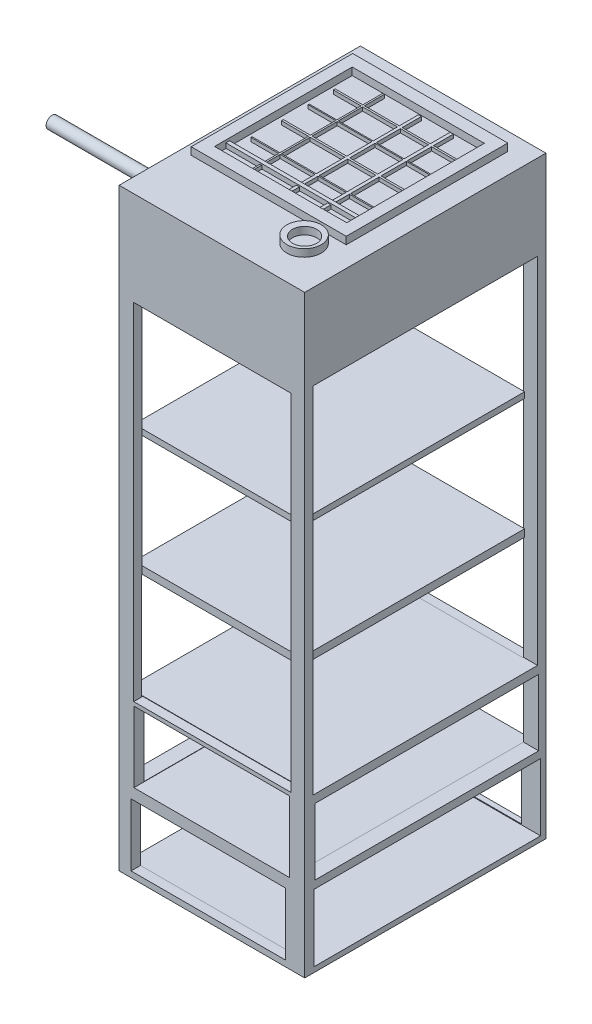
SolidWorks part; units mm, degrees
ref_plane "Front Plane" through (0, 0, 0) normal (0, 0, 1) x (1, 0, 0)
ref_plane "Top Plane" through (0, 0, 0) normal (0, 1, 0) x (1, 0, 0)
ref_plane "Right Plane" through (0, 0, 0) normal (1, 0, 0) x (0, 0, -1)
sketch "Sketch1" plane through (0, 0, 0) normal (1, 0, 0) x (0, 0, -1)
  line L1 (-32.5, 70.6888) -> (32.5, 70.6888)
  line L2 (-32.5, 70.6888) -> (-32.5, -89.3112)
  line L3 (-32.5, -89.3112) -> (32.5, -89.3112)
  line L4 (32.5, 70.6888) -> (32.5, -89.3112)
  line L5 (-30.264, 47.7422) -> (30.264, 47.7422)
  line L6 (-30.264, 47.7422) -> (-30.264, -47.7422)
  line L7 (-30.264, -47.7422) -> (30.264, -47.7422)
  line L8 (30.264, 47.7422) -> (30.264, -47.7422)
  point P0 (0, 0)
  point P7 (0, 0)
  dimension "D1" = 65
  dimension "D2" = 160
extrude "Boss-Extrude1" add sketch "Sketch1" along normal blind 50
sketch "Sketch2" plane through (0, 0, -32.5) normal (0, 0, -1) x (-1, 0, 0)
  line L1 (-46.2524, 45.3137) -> (-3.9263, 45.3137)
  line L2 (-46.2524, 45.3137) -> (-46.2524, -47.8418)
  line L3 (-46.2524, -47.8418) -> (-3.9263, -47.8418)
  line L4 (-3.9263, 45.3137) -> (-3.9263, -47.8418)
  line L5 (-46.2524, 45.3137) -> (-3.9263, -47.8418) construction
  line L6 (-46.2524, -47.8418) -> (-3.9263, 45.3137) construction
  point P0 (-25.0894, -1.2641)
extrude "Cut-Extrude1" cut sketch "Sketch2" against normal through all
sketch "Sketch3" plane through (0, -47.8418, 0) normal (0, 1, 0) x (1, 0, 0)
  line L1 (1.5977, 30.0906) -> (46.6551, 30.0906)
  line L2 (1.5977, 30.0906) -> (1.5977, -30.0603)
  line L3 (1.5977, -30.0603) -> (46.6551, -30.0603)
  line L4 (46.6551, 30.0906) -> (46.6551, -30.0603)
  line L5 (1.5977, 30.0906) -> (46.6551, -30.0603) construction
  line L6 (1.5977, -30.0603) -> (46.6551, 30.0906) construction
  point P0 (24.1264, 0.0152)
extrude "Boss-Extrude2" add sketch "Sketch3" along normal through all
sketch "Sketch4" plane through (1.5977, 0, 0) normal (-1, 0, 0) x (0, 0, 1)
  line L0 (30.264, 47.7422) -> (30.264, -47.7422) construction
  line L1 (-30.1177, 47.4229) -> (30.264, 47.4229)
  line L2 (-30.1177, 47.4229) -> (-30.1177, 14.5309)
  line L3 (-30.1177, 14.5309) -> (30.264, 14.5309)
  line L4 (30.264, 47.4229) -> (30.264, 14.5309)
  line L5 (-30.1177, 47.4229) -> (30.264, 14.5309) construction
  line L6 (-30.1177, 14.5309) -> (30.264, 47.4229) construction
  point P0 (0.0732, 30.9769)
extrude "Cut-Extrude2" cut sketch "Sketch4" against normal through all
sketch "Sketch5" plane through (46.6551, 0, 0) normal (1, 0, 0) x (0, 0, -1)
  line L1 (-30.1757, 12.9564) -> (30.2072, 12.9564)
  line L2 (-30.1757, 12.9564) -> (-30.1757, -17.4422)
  line L3 (-30.1757, -17.4422) -> (30.2072, -17.4422)
  line L4 (30.2072, 12.9564) -> (30.2072, -17.4422)
  line L5 (-30.1757, 12.9564) -> (30.2072, -17.4422) construction
  line L6 (-30.1757, -17.4422) -> (30.2072, 12.9564) construction
  point P0 (0.0157, -2.2429)
extrude "Cut-Extrude3" cut sketch "Sketch5" against normal through all
sketch "Sketch6" plane through (46.6551, 0, 0) normal (1, 0, 0) x (0, 0, -1)
  line L0 (30.0906, -17.4422) -> (30.0906, -47.7422) construction
  line L1 (-30.3597, -19.4422) -> (30.0906, -19.4422)
  line L2 (-30.3597, -19.4422) -> (-30.3597, -47.7422)
  line L3 (-30.3597, -47.7422) -> (30.0906, -47.7422)
  line L4 (30.0906, -19.4422) -> (30.0906, -47.7422)
  line L5 (-30.3597, -19.4422) -> (30.0906, -47.7422) construction
  line L6 (-30.3597, -47.7422) -> (30.0906, -19.4422) construction
  point P0 (-0.1345, -33.5922)
extrude "Cut-Extrude4" cut sketch "Sketch6" against normal through all
sketch "Sketch7" plane through (50, 0, 0) normal (1, 0, 0) x (0, 0, -1)
  line L1 (-29.7434, -49.9682) -> (30.5607, -49.9682)
  line L2 (-29.7434, -49.9682) -> (-29.7434, -67.8351)
  line L3 (-29.7434, -67.8351) -> (30.5607, -67.8351)
  line L4 (30.5607, -49.9682) -> (30.5607, -67.8351)
  line L5 (-29.7434, -49.9682) -> (30.5607, -67.8351) construction
  line L6 (-29.7434, -67.8351) -> (30.5607, -49.9682) construction
  point P0 (0.4086, -58.9016)
extrude "Cut-Extrude5" cut sketch "Sketch7" against normal through all
sketch "Sketch8" plane through (0, 0, 32.5) normal (0, 0, 1) x (1, 0, 0)
  line L1 (3.9687, -48.8665) -> (45.9067, -48.8665)
  line L2 (3.9687, -48.8665) -> (3.9687, -67.9169)
  line L3 (3.9687, -67.9169) -> (45.9067, -67.9169)
  line L4 (45.9067, -48.8665) -> (45.9067, -67.9169)
  line L5 (3.9687, -48.8665) -> (45.9067, -67.9169) construction
  line L6 (3.9687, -67.9169) -> (45.9067, -48.8665) construction
  point P0 (24.9377, -58.3917)
extrude "Cut-Extrude6" cut sketch "Sketch8" against normal through all
sketch "Sketch10" plane through (50, 0, 0) normal (1, 0, 0) x (0, 0, -1)
  line L1 (-29.9701, -69.8781) -> (31.0694, -69.8781)
  line L2 (-29.9701, -69.8781) -> (-29.9701, -87.932)
  line L3 (-29.9701, -87.932) -> (31.0694, -87.932)
  line L4 (31.0694, -69.8781) -> (31.0694, -87.932)
  line L5 (-29.9701, -69.8781) -> (31.0694, -87.932) construction
  line L6 (-29.9701, -87.932) -> (31.0694, -69.8781) construction
  point P0 (0.5496, -78.9051)
extrude "Cut-Extrude10" cut sketch "Sketch10" against normal through all
sketch "Sketch11" plane through (0, 0, -32.5) normal (0, 0, -1) x (-1, 0, 0)
  line L1 (-44.859, -70.8929) -> (-3.2128, -70.8929)
  line L2 (-44.859, -70.8929) -> (-44.859, -87.7146)
  line L3 (-44.859, -87.7146) -> (-3.2128, -87.7146)
  line L4 (-3.2128, -70.8929) -> (-3.2128, -87.7146)
  line L5 (-44.859, -70.8929) -> (-3.2128, -87.7146) construction
  line L6 (-44.859, -87.7146) -> (-3.2128, -70.8929) construction
  point P0 (-24.0359, -79.3038)
extrude "Cut-Extrude11" cut sketch "Sketch11" against normal through all
sketch "Sketch12" plane through (0, 0, 0) normal (-1, 0, 0) x (0, 0, 1)
  line L1 (-30.2872, 67.0104) -> (19.3028, 67.0104)
  line L2 (-30.2872, 67.0104) -> (-30.2872, 50.3789)
  line L3 (-30.2872, 50.3789) -> (19.3028, 50.3789)
  line L4 (19.3028, 67.0104) -> (19.3028, 50.3789)
  line L5 (-29.1753, 65.6203) -> (18.1249, 65.6203)
  line L6 (-29.1753, 65.6203) -> (-29.1753, 51.7691)
  line L7 (-29.1753, 51.7691) -> (18.1249, 51.7691)
  line L8 (18.1249, 65.6203) -> (18.1249, 51.7691)
  point P0 (2.9716, 58.6947)
  point P6 (2.6855, 58.6947)
extrude "Boss-Extrude3" add sketch "Sketch12" along normal blind 1
sketch "Sketch13" plane through (0, 0, 0) normal (-1, 0, 0) x (0, 0, 1)
  line L1 (-28.2976, 64.7358) -> (17.5421, 64.7358)
  line L2 (-28.2976, 64.7358) -> (-28.2976, 63.8455)
  line L3 (-28.2976, 63.8455) -> (17.5421, 63.8455)
  line L4 (17.5421, 64.7358) -> (17.5421, 63.8455)
  line L5 (-28.2976, 64.7358) -> (17.5421, 63.8455) construction
  line L6 (-28.2976, 63.8455) -> (17.5421, 64.7358) construction
  line L7 (-28.1792, 62.5078) -> (17.7258, 62.5078)
  line L8 (-28.1792, 62.5078) -> (-28.1792, 61.2255)
  line L9 (-28.1792, 61.2255) -> (17.7258, 61.2255)
  line L10 (17.7258, 62.5078) -> (17.7258, 61.2255)
  line L11 (-28.1792, 62.5078) -> (17.7258, 61.2255) construction
  line L12 (-28.1792, 61.2255) -> (17.7258, 62.5078) construction
  line L13 (-28.1711, 60.0546) -> (17.674, 60.0546)
  line L14 (-28.1711, 60.0546) -> (-28.1711, 59.0796)
  line L15 (-28.1711, 59.0796) -> (17.674, 59.0796)
  line L16 (17.674, 60.0546) -> (17.674, 59.0796)
  line L17 (-28.1711, 60.0546) -> (17.674, 59.0796) construction
  line L18 (-28.1711, 59.0796) -> (17.674, 60.0546) construction
  line L19 (-28.0186, 58.0084) -> (17.713, 58.0084)
  line L20 (-28.0186, 58.0084) -> (-28.0186, 57.1447)
  line L21 (-28.0186, 57.1447) -> (17.713, 57.1447)
  line L22 (17.713, 58.0084) -> (17.713, 57.1447)
  line L23 (-28.0186, 58.0084) -> (17.713, 57.1447) construction
  line L24 (-28.0186, 57.1447) -> (17.713, 58.0084) construction
  line L25 (-28.049, 56.7273) -> (17.6489, 56.7273)
  line L26 (-28.049, 56.7273) -> (-28.049, 55.6053)
  line L27 (-28.049, 55.6053) -> (17.6489, 55.6053)
  line L28 (17.6489, 56.7273) -> (17.6489, 55.6053)
  line L29 (-28.049, 56.7273) -> (17.6489, 55.6053) construction
  line L30 (-28.049, 55.6053) -> (17.6489, 56.7273) construction
  line L31 (-27.9542, 55.005) -> (17.5549, 55.005)
  line L32 (-27.9542, 55.005) -> (-27.9542, 54.2102)
  line L33 (-27.9542, 54.2102) -> (17.5549, 54.2102)
  line L34 (17.5549, 55.005) -> (17.5549, 54.2102)
  line L35 (-27.9542, 55.005) -> (17.5549, 54.2102) construction
  line L36 (-27.9542, 54.2102) -> (17.5549, 55.005) construction
  line L37 (-28.0211, 53.4431) -> (17.3054, 53.4431)
  line L38 (-28.0211, 53.4431) -> (-28.0211, 52.6483)
  line L39 (-28.0211, 52.6483) -> (17.3054, 52.6483)
  line L40 (17.3054, 53.4431) -> (17.3054, 52.6483)
  line L41 (-28.0211, 53.4431) -> (17.3054, 52.6483) construction
  line L42 (-28.0211, 52.6483) -> (17.3054, 53.4431) construction
  point P0 (-5.3777, 64.2907)
  point P5 (-5.2486, 59.5671)
  point P6 (-5.2267, 61.8666)
  point P15 (-5.1528, 57.5766)
  point P20 (-5.2, 56.1663)
  point P25 (-5.1996, 54.6076)
  point P30 (-5.3579, 53.0457)
extrude "Boss-Extrude4" add sketch "Sketch13" along normal blind 1
sketch "Sketch17" plane through (0, 0, 0) normal (-1, 0, 0) x (0, 0, 1)
  circle A0 centre (22.5775, 66.4593) radius 1.6078
extrude "Boss-Extrude7" add sketch "Sketch17" along normal blind 28
sketch "Sketch18" plane through (0, -67.9169, 0) normal (0, 1, 0) x (1, 0, 0)
  line L1 (19.2354, 28.2996) -> (8.2979, 28.2996)
  line L2 (19.2354, 28.2996) -> (19.2354, 11.6786)
  line L3 (19.2354, 11.6786) -> (8.2979, 11.6786)
  line L4 (8.2979, 28.2996) -> (8.2979, 11.6786)
  line L5 (19.2354, 28.2996) -> (8.2979, 11.6786) construction
  line L6 (19.2354, 11.6786) -> (8.2979, 28.2996) construction
  point P0 (13.7666, 19.9891)
extrude "Boss-Extrude9" add sketch "Sketch18" along normal blind 10
sketch "Sketch19" plane through (0, 70.6888, 0) normal (0, 1, 0) x (1, 0, 0)
  circle A0 centre (38.4512, -21.1125) radius 4.6271
  circle A1 centre (38.8925, -21.4164) radius 3.27
extrude "Boss-Extrude10" add sketch "Sketch19" along normal blind 2
sketch "Sketch20" plane through (0, 70.6888, 0) normal (0, 1, 0) x (1, 0, 0)
  line L1 (44.496, 27.7166) -> (2.7156, 27.7166)
  line L2 (44.496, 27.7166) -> (44.496, -15.8024)
  line L3 (44.496, -15.8024) -> (2.7156, -15.8024)
  line L4 (2.7156, 27.7166) -> (2.7156, -15.8024)
  line L5 (44.496, 27.7166) -> (2.7156, -15.8024) construction
  line L6 (44.496, -15.8024) -> (2.7156, 27.7166) construction
  line L7 (41.4078, 24.4999) -> (5.8038, 24.4999)
  line L8 (41.4078, 24.4999) -> (41.4078, -12.5857)
  line L9 (41.4078, -12.5857) -> (5.8038, -12.5857)
  line L10 (5.8038, 24.4999) -> (5.8038, -12.5857)
  line L11 (41.4078, 24.4999) -> (5.8038, -12.5857) construction
  line L12 (41.4078, -12.5857) -> (5.8038, 24.4999) construction
  point P0 (23.6058, 5.9571)
  point P7 (23.6058, 5.9571)
extrude "Boss-Extrude11" add sketch "Sketch20" along normal blind 2
sketch "Sketch21" plane through (0, 70.6888, 0) normal (0, 1, 0) x (1, 0, 0)
  line L1 (40.4992, 17.61) -> (7.6115, 17.61)
  line L2 (40.4992, 17.61) -> (40.4992, 18.0971)
  line L3 (40.4992, 18.0971) -> (7.6115, 18.0971)
  line L4 (7.6115, 17.61) -> (7.6115, 18.0971)
  line L5 (40.4992, 17.61) -> (7.6115, 18.0971) construction
  line L6 (40.4992, 18.0971) -> (7.6115, 17.61) construction
  line L7 (40.4707, 10.775) -> (7.6571, 10.775)
  line L8 (40.4707, 10.775) -> (40.4707, 11.0739)
  line L9 (40.4707, 11.0739) -> (7.6571, 11.0739)
  line L10 (7.6571, 10.775) -> (7.6571, 11.0739)
  line L11 (40.4707, 10.775) -> (7.6571, 11.0739) construction
  line L12 (40.4707, 11.0739) -> (7.6571, 10.775) construction
  line L13 (40.906, 3.9577) -> (7.8021, 3.9577)
  line L14 (40.906, 3.9577) -> (40.906, 3.4384)
  line L15 (40.906, 3.4384) -> (7.8021, 3.4384)
  line L16 (7.8021, 3.9577) -> (7.8021, 3.4384)
  line L17 (40.906, 3.9577) -> (7.8021, 3.4384) construction
  line L18 (40.906, 3.4384) -> (7.8021, 3.9577) construction
  line L19 (40.4476, -4.5868) -> (7.5662, -4.5868)
  line L20 (40.4476, -4.5868) -> (40.4476, -4.2522)
  line L21 (40.4476, -4.2522) -> (7.5662, -4.2522)
  line L22 (7.5662, -4.5868) -> (7.5662, -4.2522)
  line L23 (40.4476, -4.5868) -> (7.5662, -4.2522) construction
  line L24 (40.4476, -4.2522) -> (7.5662, -4.5868) construction
  point P0 (24.0553, 17.8536)
  point P5 (24.354, 3.6981)
  point P6 (24.0639, 10.9244)
  point P15 (24.0069, -4.4195)
extrude "Boss-Extrude12" add sketch "Sketch21" along normal blind 1
sketch "Sketch22" plane through (0, 70.6888, 0) normal (0, 1, 0) x (1, 0, 0)
  line L1 (34.0968, 23.4506) -> (33.2223, 23.4506)
  line L2 (34.0968, 23.4506) -> (34.0968, -12.1702)
  line L3 (34.0968, -12.1702) -> (33.2223, -12.1702)
  line L4 (33.2223, 23.4506) -> (33.2223, -12.1702)
  line L5 (34.0968, 23.4506) -> (33.2223, -12.1702) construction
  line L6 (34.0968, -12.1702) -> (33.2223, 23.4506) construction
  line L7 (24.8719, 23.2806) -> (25.6704, 23.2806)
  line L8 (24.8719, 23.2806) -> (24.8719, -12.1702)
  line L9 (24.8719, -12.1702) -> (25.6704, -12.1702)
  line L10 (25.6704, 23.2806) -> (25.6704, -12.1702)
  line L11 (24.8719, 23.2806) -> (25.6704, -12.1702) construction
  line L12 (24.8719, -12.1702) -> (25.6704, 23.2806) construction
  line L13 (15.0677, 23.5067) -> (15.4979, 23.5067)
  line L14 (15.0677, 23.5067) -> (15.0677, -12.1702)
  line L15 (15.0677, -12.1702) -> (15.4979, -12.1702)
  line L16 (15.4979, 23.5067) -> (15.4979, -12.1702)
  line L17 (15.0677, 23.5067) -> (15.4979, -12.1702) construction
  line L18 (15.0677, -12.1702) -> (15.4979, 23.5067) construction
  point P0 (33.6596, 5.6402)
  point P5 (25.2711, 5.5552)
  point P11 (15.2828, 5.6682)
extrude "Boss-Extrude13" add sketch "Sketch22" along normal blind 1
sketch "Sketch23" plane through (41.4078, 0, 0) normal (-1, 0, 0) x (0, 0, 1)
  line L1 (8.5733, 72.0321) -> (9.5687, 72.0321)
  line L2 (8.5733, 72.0321) -> (8.5733, 70.7591)
  line L3 (8.5733, 70.7591) -> (9.5687, 70.7591)
  line L4 (9.5687, 72.0321) -> (9.5687, 70.7591)
  line L5 (8.5733, 72.0321) -> (9.5687, 70.7591) construction
  line L6 (8.5733, 70.7591) -> (9.5687, 72.0321) construction
  point P0 (9.071, 71.3956)
extrude "Boss-Extrude14" add sketch "Sketch23" along normal blind 37
